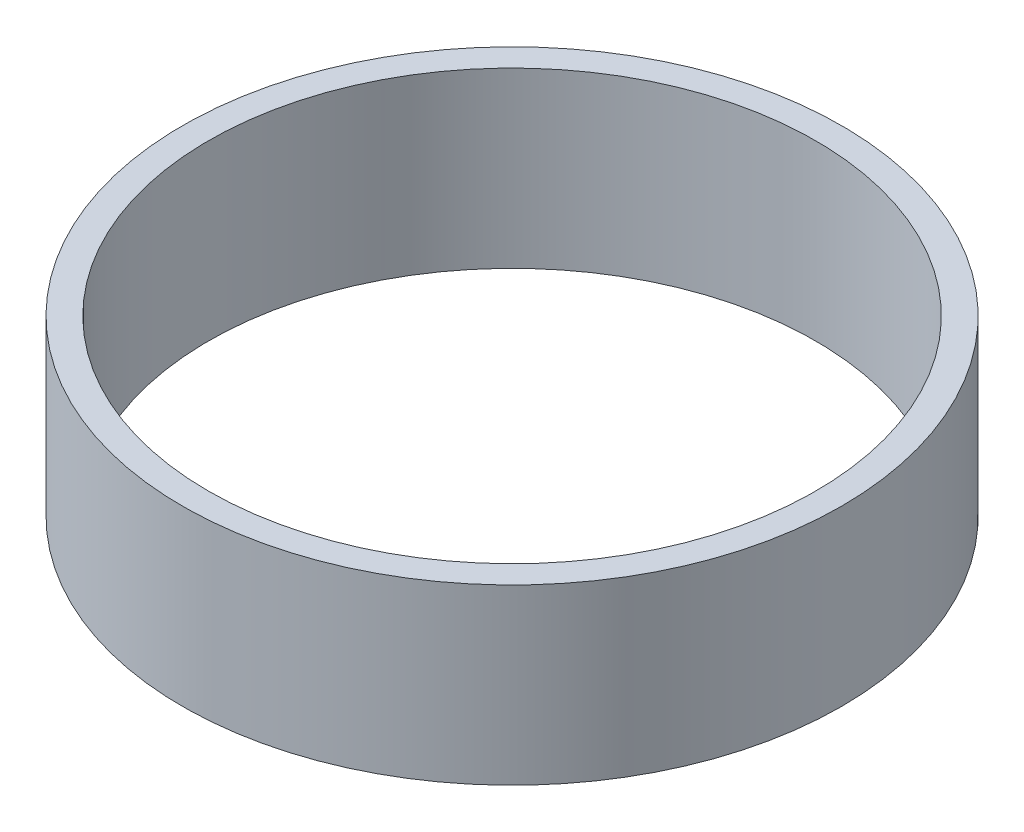
SolidWorks part; units mm, degrees
material "橡胶"
ref_plane "前视基准面" through (0, 0, 0) normal (0, 0, 1) x (1, 0, 0)
ref_plane "上视基准面" through (0, 0, 0) normal (0, 1, 0) x (1, 0, 0)
ref_plane "右视基准面" through (0, 0, 0) normal (1, 0, 0) x (0, 0, -1)
sketch "草图1" plane through (0, 0, 0) normal (0, 1, 0) x (1, 0, 0)
  circle A0 centre (0, 0) radius 35
  dimension "D1" = 70
extrude "拉伸-薄壁1" add sketch "草图1" along normal blind 20 thin
